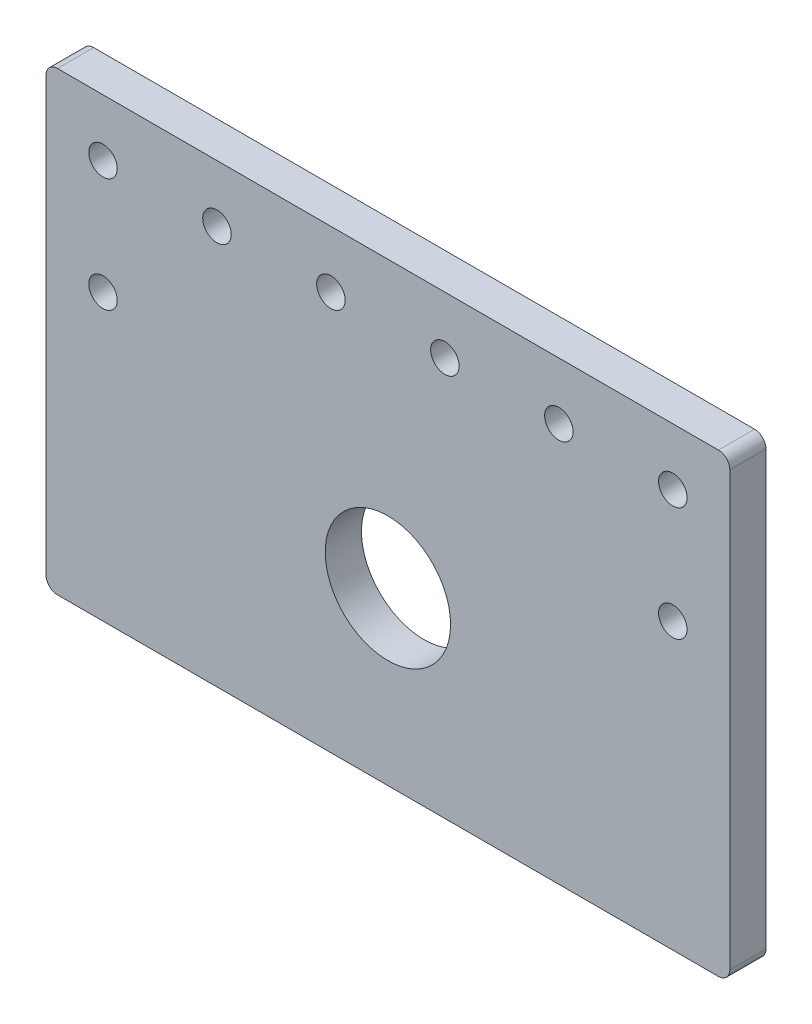
SolidWorks part; units mm, degrees
ref_plane "Front Plane" through (0, 0, 0) normal (0, 0, 1) x (1, 0, 0)
ref_plane "Top Plane" through (0, 0, 0) normal (0, 1, 0) x (1, 0, 0)
ref_plane "Right Plane" through (0, 0, 0) normal (1, 0, 0) x (0, 0, -1)
sketch "Sketch1" plane through (0, 0, 0) normal (0, 0, 1) x (1, 0, 0)
  line L0 (-60, 30) -> (60, 30) construction
  line L1 (-60, 40) -> (60, 40)
  line L2 (-60, 40) -> (-60, -40)
  line L3 (-60, -40) -> (60, -40)
  line L4 (60, 40) -> (60, -40)
  line L5 (-60, 40) -> (60, -40) construction
  line L6 (-60, -40) -> (60, 40) construction
  line L7 (-50, 40) -> (-50, -40) construction
  line L8 (0, -10) -> (-23.5, -10) construction
  line L9 (-23.5, -10) -> (-23.5, 13.5) construction
  circle A0 centre (-50, 30) radius 2.5
  circle A1 centre (-30, 30) radius 2.5
  circle A2 centre (-10, 30) radius 2.5
  circle A3 centre (10, 30) radius 2.5
  circle A4 centre (30, 30) radius 2.5
  circle A5 centre (50, 30) radius 2.5
  circle A6 centre (-50, 10) radius 2.5
  circle A7 centre (50, 10) radius 2.5
  circle A8 centre (0, -10) radius 11
  point P0 (0, 0)
  point P10 (-50, 30)
  point P41 (0, -10)
  dimension "D5" = 5
  dimension "D9" = 22
  dimension "D1" = 120
  dimension "D2" = 80
  dimension "D3" = 10
  dimension "D4" = 10
  dimension "D8" = 40
  dimension "D10" = 23.5
  dimension "D11" = 23.5
  dimension "D6" = 6
  dimension "D7" = 2
extrude "Boss-Extrude1" add sketch "Sketch1" along normal blind 6.35
fillet "Fillet1" radius 2 4 edges at (60, -40, 3.175) (-60, -40, 3.175) (60, 40, 3.175) (-60, 40, 3.175)
